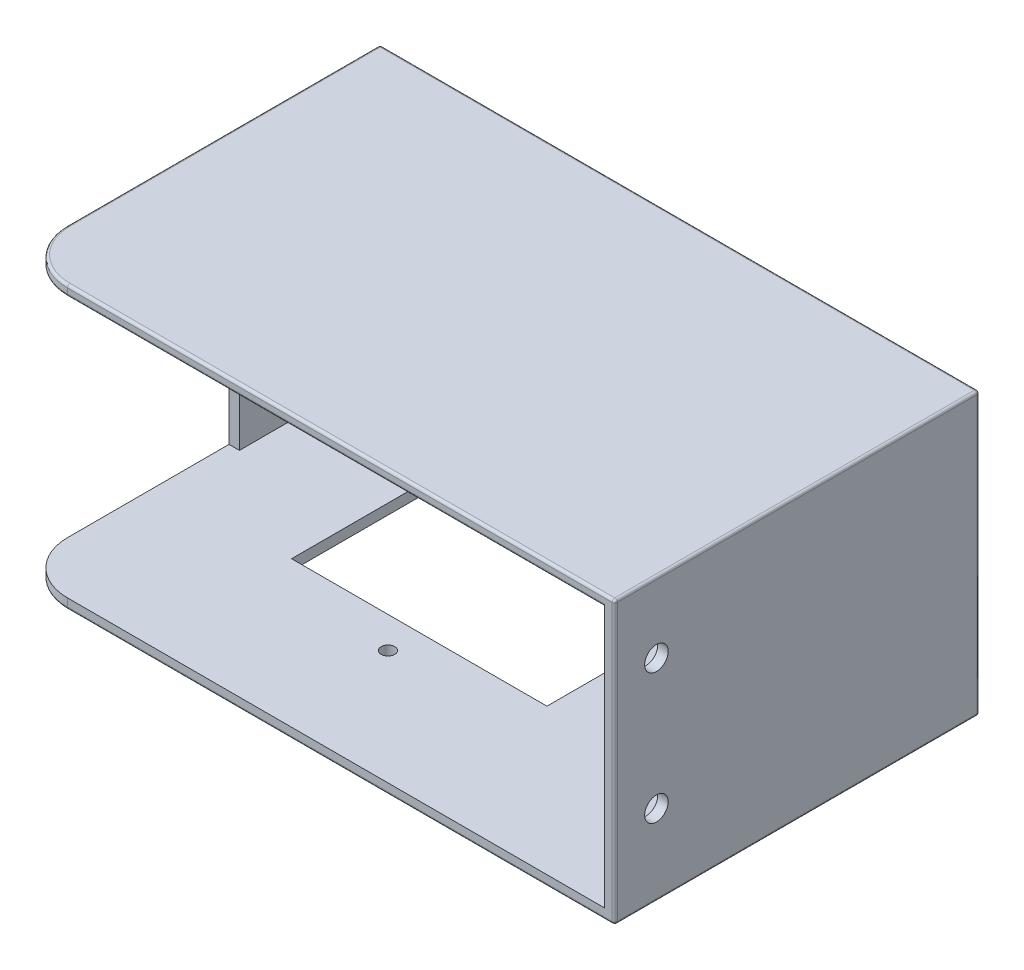
SolidWorks part; units mm, degrees
ref_plane "Alzado" through (0, 0, 0) normal (0, 0, 1) x (1, 0, 0)
ref_plane "Planta" through (0, 0, 0) normal (0, 1, 0) x (1, 0, 0)
ref_plane "Vista lateral" through (0, 0, 0) normal (1, 0, 0) x (0, 0, -1)
ref_plane "Plano1" through (0, -27, 0) normal (0, -1, 0) x (1, 0, 0)
sketch "Croquis1" plane through (0, -27, 0) normal (0, -1, 0) x (1, 0, 0)
  line L0 (-57.5, 0) -> (57.5, 0)
  line L1 (57.5, 0) -> (57.5, 70)
  line L2 (57.5, 70) -> (-57.5, 70)
  line L3 (-57.5, 70) -> (-57.5, 0)
extrude "Saliente-Extruir1" add sketch "Croquis1" against normal blind 54
ref_plane "Plano2" through (0, 25, 0) normal (0, 1, 0) x (1, 0, 0)
sketch "Croquis2" plane through (0, 25, 0) normal (0, 1, 0) x (1, 0, 0)
  line L0 (-57.5, -29) -> (-57.5, -70)
  line L1 (-57.5, -70) -> (55.5, -70)
  line L2 (55.5, -70) -> (55.5, -2)
  line L3 (55.5, -2) -> (-55.5, -2)
  line L4 (-55.5, -2) -> (-55.5, -29)
  line L5 (-55.5, -29) -> (-57.5, -29)
extrude "Cortar-Extruir1" cut sketch "Croquis2" against normal blind 50
sketch "Croquis3" plane through (0, -25, 0) normal (0, 1, 0) x (-1, 0, 0)
  line L0 (-16.5, 14) -> (32.5, 14)
  line L1 (32.5, 14) -> (32.5, 42)
  line L2 (32.5, 42) -> (-16.5, 42)
  line L3 (-16.5, 42) -> (-16.5, 14)
extrude "Cortar-Extruir2" cut sketch "Croquis3" against normal through all
sketch "Croquis4" plane through (0, 0, 0) normal (0, 0, -1) x (-1, 0, 0)
  line L0 (-4.5, 15) -> (-16.5, 15)
  line L1 (-16.5, -1) -> (-4.5, -1)
  arc A0 (-16.5, 15) -> (-16.5, -1) centre (-16.5, 7) ccw
  arc A1 (-4.5, -1) -> (-4.5, 15) centre (-4.5, 7) ccw
extrude "Cortar-Extruir3" cut sketch "Croquis4" against normal through all
hole_wizard "Diámetro de taladro Ø4.5 (4.5)1" positions "Croquis6" profile "Croquis5" hole size "Ø4.5" standard "Ansi Metric"
sketch "Croquis6" plane through (57.5, 0, 0) normal (1, 0, 0) x (0, 0, -1)
  point P0 (-62, -11.5)
  point P1 (-62, 13.5)
sketch "Croquis5" plane through (57.5, -11.5, 62) normal (0, 1, 0) x (0, 0, -1)
  line L0 (0, 0) -> (0, 115)
  line L1 (0, 115) -> (2.25, 115)
  line L2 (2.25, 115) -> (2.25, 0)
  line L5 (2.25, 0) -> (0, 0)
  line L11 (0, -6.35) -> (0, 107.95) construction
  dimension "Diámetro de taladro hasta el siguiente" = 4.5
  dimension "Profundidad de taladro hasta el siguiente" = 115
hole_wizard "Diámetro de taladro Ø2.6 (2.6)1" positions "Croquis8" profile "Croquis7" hole size "Ø2.6" standard "Ansi Metric"
sketch "Croquis8" plane through (0, -27, 0) normal (0, -1, 0) x (-1, 0, 0)
  point P0 (8, -48)
  point P1 (8, -8)
sketch "Croquis7" plane through (-8, -27, 48) normal (1, 0, 0) x (0, 0, -1)
  line L0 (0, 0) -> (0, 2)
  line L1 (0, 2) -> (1.3, 2)
  line L2 (1.3, 2) -> (1.3, 0)
  line L5 (1.3, 0) -> (0, 0)
  line L11 (0, -6.35) -> (0, 107.95) construction
  dimension "Diámetro de taladro hasta el siguiente" = 2.6
  dimension "Profundidad de taladro hasta el siguiente" = 2
fillet "Redondeo1" radius 10 2 edges at (-57.5, 26, 70) (-57.5, -26, 70)
fillet "Redondeo2" radius 0.5 16 edges at (0, -27, 0) (-57.5, 0, 0) (57.5, -27, 35) (-57.5, -27, 30) (-54.5711, -27, 67.0711) (5, -27, 70) (57.5, 0, 0) (-57.5, 27, 30) (-54.5711, 27, 67.0711) (5, 27, 70) (0, 27, 0) (57.5, 0, 70) (57.5, 27, 35) (-57.5, 25, 44.5) (-54.5711, 25, 67.0711) (4, 25, 70)
